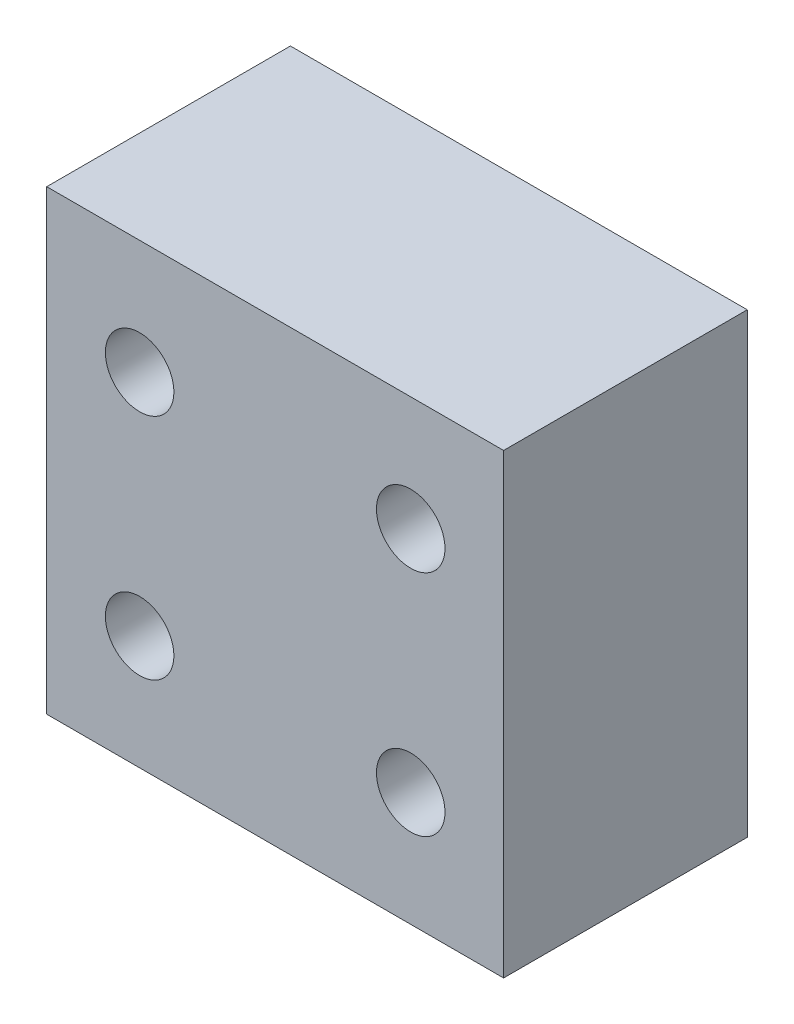
SolidWorks part; units mm, degrees
ref_plane "前视基准面" through (0, 0, 0) normal (0, 0, 1) x (1, 0, 0)
ref_plane "上视基准面" through (0, 0, 0) normal (0, 1, 0) x (1, 0, 0)
ref_plane "右视基准面" through (0, 0, 0) normal (1, 0, 0) x (0, 0, -1)
sketch "草图1" plane through (0, 0, 0) normal (0, 0, 1) x (1, 0, 0)
  line L1 (-15, 15) -> (15, 15)
  line L2 (-15, 15) -> (-15, -15)
  line L3 (-15, -15) -> (15, -15)
  line L4 (15, 15) -> (15, -15)
  line L5 (0, -15) -> (0, 15) construction
  line L6 (-15, 0) -> (15, 0) construction
  point P0 (0, 0)
  dimension "D1" = 30
  dimension "D2" = 30
extrude "凸台-拉伸1" add sketch "草图1" along normal blind 16
sketch "草图3" plane through (0, 0, 16) normal (0, 0, 1) x (1, 0, 0)
  line L0 (-15, 15) -> (15, -15)
  line L1 (15, 15) -> (-15, -15)
  point P8 (0, 0)
sketch "草图4" plane through (0, 0, 16) normal (0, 0, 1) x (1, 0, 0)
  circle A0 centre (8.9, 7.5) radius 2.25
  circle A1 centre (8.9, -7.5) radius 2.25
  circle A2 centre (-8.9, 7.5) radius 2.25
  circle A3 centre (-8.9, -7.5) radius 2.25
extrude "切除-拉伸2" cut sketch "草图4" against normal through all
